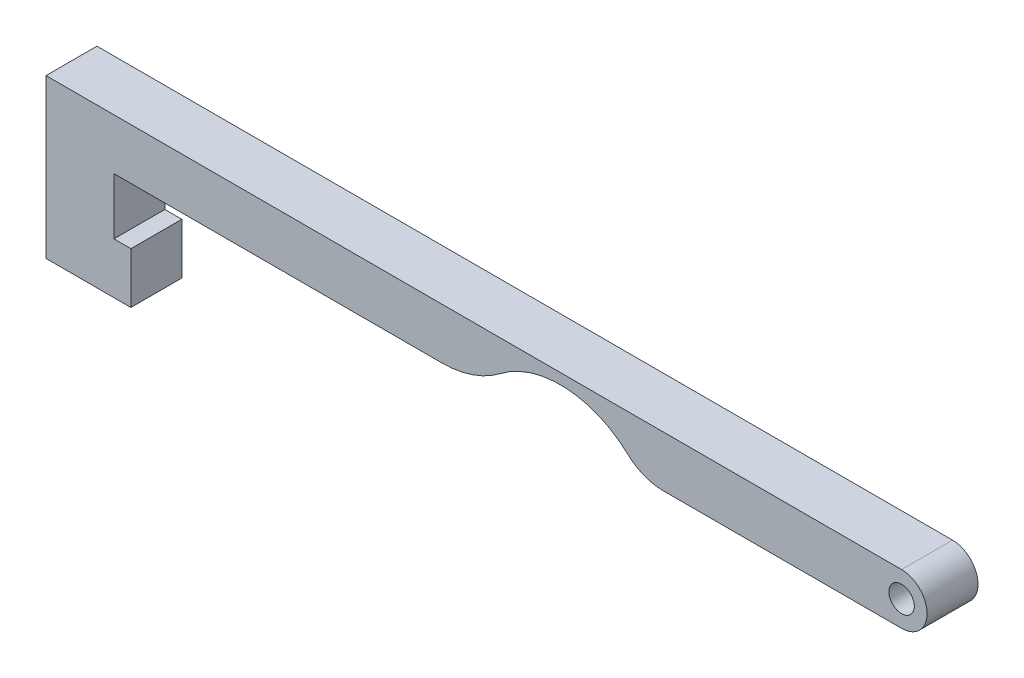
SolidWorks part; units mm, degrees
ref_plane "Front Plane" through (0, 0, 0) normal (0, 0, 1) x (1, 0, 0)
ref_plane "Top Plane" through (0, 0, 0) normal (0, 1, 0) x (1, 0, 0)
ref_plane "Right Plane" through (0, 0, 0) normal (1, 0, 0) x (0, 0, -1)
sketch "Sketch1" plane through (0, 0, 0) normal (0, 0, 1) x (1, 0, 0)
  line L0 (50, 0) -> (0, 0)
  line L1 (0, 0) -> (0, 93.2849)
  line L2 (0, 93.2849) -> (503.8528, 93.2849)
  line L4 (503.8528, 63.2849) -> (363.3502, 63.2849)
  line L5 (233.0366, 63.2849) -> (40, 63.2849)
  line L6 (40, 63.2849) -> (40, 30)
  line L7 (40, 30) -> (50, 30)
  line L8 (50, 30) -> (50, 0)
  arc A0 (363.3502, 63.2849) -> (342.6767, 71.4265) centre (363.3502, 93.6034) cw
  arc A1 (342.6767, 71.4265) -> (267.3947, 74.9777) centre (302.9412, 28.8014) ccw
  arc A2 (267.3947, 74.9777) -> (233.0366, 63.2849) centre (233.0366, 119.6104) cw
  circle A3 centre (503.8528, 78.2849) radius 7.5
  arc A4 (503.8528, 63.2849) -> (503.8528, 93.2849) centre (503.8528, 78.2849) ccw
  point P17 (0, 0)
  dimension "D5" = 15
  dimension "D6" = 30
  dimension "D1" = 40
  dimension "D2" = 10
  dimension "D3" = 30
  dimension "D4" = 30
extrude "Boss-Extrude1" add sketch "Sketch1" along normal blind 30
